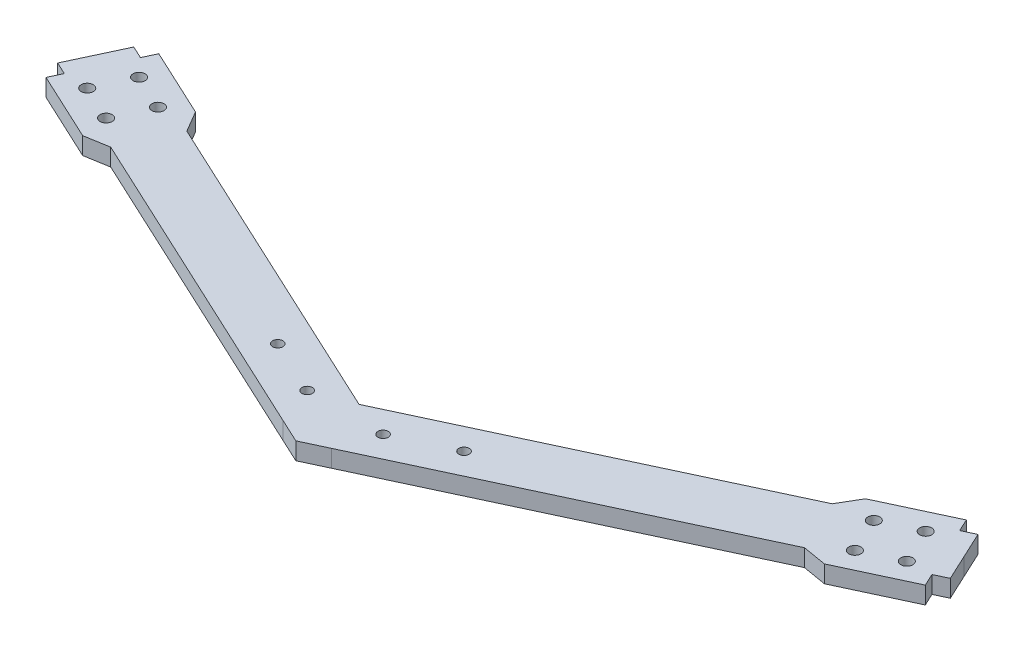
SolidWorks part; units mm, degrees
material "Thornel Mat VMA"
ref_plane "Front Plane" through (0, 0, 0) normal (0, 0, 1) x (1, 0, 0)
ref_plane "Top Plane" through (0, 0, 0) normal (0, 1, 0) x (1, 0, 0)
ref_plane "Right Plane" through (0, 0, 0) normal (1, 0, 0) x (0, 0, -1)
sketch "Sketch1" plane through (0, 0, 0) normal (0, 1, 0) x (1, 0, 0)
  line L0 (0, 0) -> (0, 18.32) construction
  line L1 (0, 18.32) -> (-93.531, 61.9342)
  line L2 (-93.531, 61.9342) -> (-97.0996, 68.0143)
  line L3 (-97.0996, 68.0143) -> (-117.0383, 77.3119)
  line L4 (-117.0383, 77.3119) -> (-118.7288, 73.6867)
  line L5 (-118.7288, 73.6867) -> (-122.354, 75.3771)
  line L6 (-122.354, 75.3771) -> (-125.8618, 67.8548)
  line L7 (0, 9.16) -> (-125.8618, 67.8548) construction
  line L8 (-7.0173, 3.2725) -> (-100.5457, 46.8922)
  line L9 (-125.7448, 58.642) -> (-129.3699, 60.3326)
  line L10 (-127.4355, 55.0168) -> (-125.7448, 58.642)
  line L11 (-129.3699, 60.3326) -> (-125.8618, 67.8548)
  line L12 (-107.4973, 45.7181) -> (-127.4355, 55.0168)
  line L13 (-100.5457, 46.8922) -> (-107.4973, 45.7181)
  line L14 (-7.0173, 3.2725) -> (0, 0)
  line L15 (7.0173, 3.2725) -> (0, 0)
  line L16 (7.0173, 3.2725) -> (100.5457, 46.8922)
  line L17 (0, 9.16) -> (125.8618, 67.8548) construction
  line L18 (107.4973, 45.7181) -> (127.4355, 55.0168)
  line L19 (129.3699, 60.3326) -> (125.8618, 67.8548)
  line L20 (122.354, 75.3771) -> (125.8618, 67.8548)
  line L21 (118.7288, 73.6867) -> (122.354, 75.3771)
  line L22 (117.0383, 77.3119) -> (118.7288, 73.6867)
  line L23 (97.0996, 68.0143) -> (117.0383, 77.3119)
  line L24 (0, 18.32) -> (93.531, 61.9342)
  line L25 (127.4355, 55.0168) -> (125.7448, 58.642)
  line L26 (100.5457, 46.8922) -> (107.4973, 45.7181)
  line L27 (93.531, 61.9342) -> (97.0996, 68.0143)
  line L28 (125.7448, 58.642) -> (129.3699, 60.3326)
  dimension "D1" = 18.32
  dimension "D2" = 103.2
  dimension "D3" = 65
  dimension "D4" = 7.05
  dimension "D5" = 145.41
  dimension "D6" = 22
  dimension "D7" = 4
  dimension "D8" = 90
  dimension "D9" = 4
  dimension "D10" = 8.3
  dimension "D11" = 90
extrude "Boss-Extrude1" add sketch "Sketch1" along normal mid plane 5
sketch "Sketch2" plane through (0, 2.5, 0) normal (0, 1, 0) x (1, 0, 0)
  line L0 (0, 0) -> (0, 18.32) construction
  line L1 (0, 18.32) -> (-93.531, 61.9342) construction
  line L2 (93.531, 61.9342) -> (0, 18.32) construction
  circle A0 centre (-11, 14.2913) radius 1.5
  circle A1 centre (11, 14.2913) radius 1.5
  circle A2 centre (-27, 21.7523) radius 1.5
  circle A3 centre (27, 21.7523) radius 1.5
  dimension "D1" = 3
  dimension "D2" = 3
  dimension "D3" = 22
  dimension "D7" = 3
  dimension "D4" = 11
  dimension "D5" = 8.3
  dimension "D6" = 8.3
  dimension "D8" = 8.3
  dimension "D9" = 27
extrude "Cut-Extrude1" cut sketch "Sketch2" against normal through all
sketch "Sketch3" plane through (0, 2.5, 0) normal (0, 1, 0) x (1, 0, 0)
  line L0 (-122.354, 75.3771) -> (-125.8618, 67.8548) construction
  line L1 (-114.0015, 68.5624) -> (-118.7802, 58.3144) construction
  line L2 (-114.0015, 68.5624) -> (-103.7421, 63.7784) construction
  line L3 (-103.7421, 63.7784) -> (-108.5217, 53.5301) construction
  line L4 (-97.0996, 68.0143) -> (-117.0383, 77.3119) construction
  line L5 (-118.7802, 58.3144) -> (-108.5217, 53.5301) construction
  line L6 (-127.4355, 55.0168) -> (-107.4973, 45.7181) construction
  line L8 (0, 18.32) -> (0, 0) construction
  line L9 (-125.8618, 67.8548) -> (-102.1601, 56.8008) construction
  line L10 (-125.8618, 67.8548) -> (-129.3699, 60.3326) construction
  circle A0 centre (-114.0015, 68.5624) radius 1.75
  circle A1 centre (-118.7802, 58.3144) radius 1.75
  circle A2 centre (-103.7421, 63.7784) radius 1.75
  circle A3 centre (-108.5217, 53.5301) radius 1.75
  circle A4 centre (103.7421, 63.7784) radius 1.75
  circle A5 centre (108.5217, 53.5301) radius 1.75
  circle A6 centre (118.7802, 58.3144) radius 1.75
  circle A7 centre (114.0015, 68.5624) radius 1.75
  circle A8 centre (-111.2612, 61.0464) radius 8 construction
  point P33 (0, 0)
  point P34 (0, 0)
  point P35 (0, 0)
  point P36 (-114.0015, 68.5624)
  dimension "D1" = 3.5
  dimension "D4" = 12.3
  dimension "D5" = 8
  dimension "D3" = 16
  dimension "D6" = 16.11
  dimension "D7" = 11.3074
  dimension "D2" = 10.45
extrude "Cut-Extrude2" cut sketch "Sketch3" against normal through all
